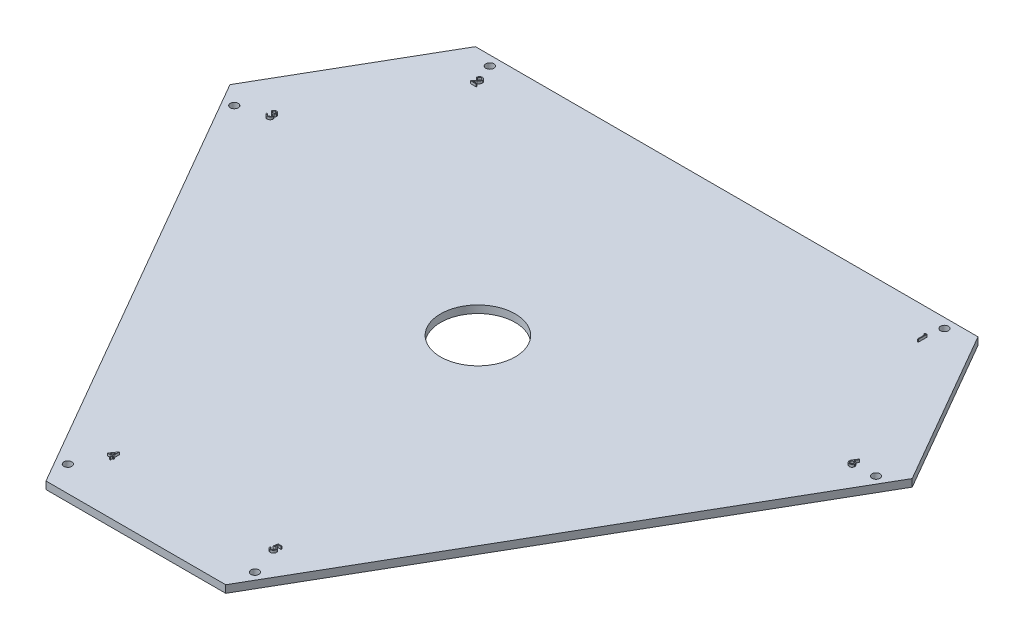
SolidWorks part; units mm, degrees
ref_plane "Front Plane" through (0, 0, 0) normal (0, 0, 1) x (1, 0, 0)
ref_plane "Top Plane" through (0, 0, 0) normal (0, 1, 0) x (1, 0, 0)
ref_plane "Right Plane" through (0, 0, 0) normal (1, 0, 0) x (0, 0, -1)
sketch "Sketch1" plane through (0, 0, 0) normal (0, 1, 0) x (1, 0, 0)
  line L0 (0, 0) -> (142.1197, 0) construction
  line L9 (0, 0) -> (0, 142.1197) construction
  line L15 (0, 0) -> (123.0793, 71.0598) construction
  line L16 (0, 0) -> (91.3528, 108.87) construction
  line L17 (0, 0) -> (139.9606, 24.6788) construction
  line L18 (0, 0) -> (48.6078, -133.5488) construction
  line L19 (0, 0) -> (-48.6078, -133.5488) construction
  line L20 (0, 0) -> (-139.9606, 24.6788) construction
  line L21 (0, 0) -> (-91.3528, 108.87) construction
  line L35 (91.3528, 108.87) -> (91.3528, 100) construction
  line L36 (91.3528, 100) -> (91.3528, 96.15) construction
  line L37 (132.2789, 29.1138) -> (128.9447, 31.0388) construction
  line L42 (139.9606, 24.6788) -> (132.2789, 29.1138) construction
  line L43 (100.9852, 100) -> (-100.9852, 100)
  line L77 (36.1099, -137.4557) -> (137.0951, 37.4557)
  line L78 (0, 0) -> (48.6078, -133.5488) construction
  line L79 (0, 0) -> (0, -142.1197) construction
  line L80 (0, 0) -> (-48.6078, -133.5488) construction
  line L81 (-48.6078, -133.5488) -> (-40.9262, -129.1138) construction
  line L82 (-40.9262, -129.1138) -> (-37.592, -127.1888) construction
  line L83 (48.6078, -133.5488) -> (40.9262, -129.1138) construction
  line L84 (40.9262, -129.1138) -> (37.592, -127.1888) construction
  line L85 (-137.0951, 37.4557) -> (-36.1099, -137.4557)
  line L86 (0, 0) -> (-139.9606, 24.6788) construction
  line L87 (0, 0) -> (-123.0793, 71.0598) construction
  line L88 (0, 0) -> (-91.3528, 108.87) construction
  line L89 (-91.3528, 108.87) -> (-91.3528, 100) construction
  line L90 (-91.3528, 100) -> (-91.3528, 96.15) construction
  line L91 (-139.9606, 24.6788) -> (-132.2789, 29.1138) construction
  line L92 (-132.2789, 29.1138) -> (-128.9447, 31.0388) construction
  line L93 (100.9852, 100) -> (137.0951, 37.4557)
  line L95 (-100.9852, 100) -> (-137.0951, 37.4557)
  line L98 (-36.1099, -137.4557) -> (36.1099, -137.4557)
  circle A31 centre (0, 0) radius 142.1197 construction
  circle A32 centre (0, 0) radius 15
  circle A43 centre (91.3528, 96.15) radius 1.6
  circle A44 centre (128.9447, 31.0388) radius 1.6
  circle A49 centre (91.3528, 96.15) radius 4 construction
  circle A50 centre (128.9447, 31.0388) radius 4 construction
  circle A55 centre (37.592, -127.1888) radius 1.6
  circle A56 centre (37.592, -127.1888) radius 4 construction
  circle A57 centre (-37.592, -127.1888) radius 4 construction
  circle A58 centre (-37.592, -127.1888) radius 1.6
  circle A59 centre (-128.9447, 31.0388) radius 1.6
  circle A60 centre (-128.9447, 31.0388) radius 4 construction
  circle A61 centre (-91.3528, 96.15) radius 4 construction
  circle A62 centre (-91.3528, 96.15) radius 1.6
  point P12 (-101.0203, 10.9895)
  point P14 (-40.993, -92.9809)
  point P15 (0, 0)
  point P16 (40.993, -92.9809)
  point P18 (101.0203, 10.9895)
  point P19 (0, 0)
  point P36 (1.4434, 2.3094)
  point P38 (0, 0)
  point P44 (0, 0)
  point P45 (0, 0)
  point P61 (0, 0)
  dimension "D1" = 3
  dimension "D6" = 12.72
  dimension "D11" = 284.2394
  dimension "D4" = 30
  dimension "D8" = 8
  dimension "D7" = 3.2
  dimension "D2" = 20
  dimension "D3" = 30
  dimension "D5" = 8.87
  dimension "D9" = 3
  dimension "D10" = 100
extrude "Boss-Extrude1" add sketch "Sketch1" along normal blind 3
sketch "Sketch2" plane through (0, 3, 0) normal (0, 1, 0) x (1, 0, 0)
  circle A0 centre (91.3528, 96.15) radius 1.6 construction
  circle A1 centre (-91.3528, 96.15) radius 1.6 construction
  circle A2 centre (-128.9447, 31.0388) radius 1.6 construction
  circle A3 centre (-37.592, -127.1888) radius 1.6 construction
  circle A4 centre (37.592, -127.1888) radius 1.6 construction
  circle A5 centre (128.9447, 31.0388) radius 1.6 construction
  text T0 "1\r\n"
  text T1 "2\r\n"
  text T2 "3\r\n"
  text T3 "4\r\n"
  text T4 "5\r\n"
  text T5 "6\r\n"
  point P21 (0, 0)
  point P22 (0, 0)
  dimension "D2" = 2
  dimension "D1" = 10
  dimension "D3" = 10
  dimension "D4" = 2
  dimension "D5" = 10
  dimension "D6" = 2
  dimension "D7" = 10
  dimension "D8" = 5
  dimension "D9" = 5
  dimension "D10" = 10
  dimension "D11" = 10
  dimension "D12" = 2
extrude "Boss-Extrude2" add sketch "Sketch2" along normal blind 1
